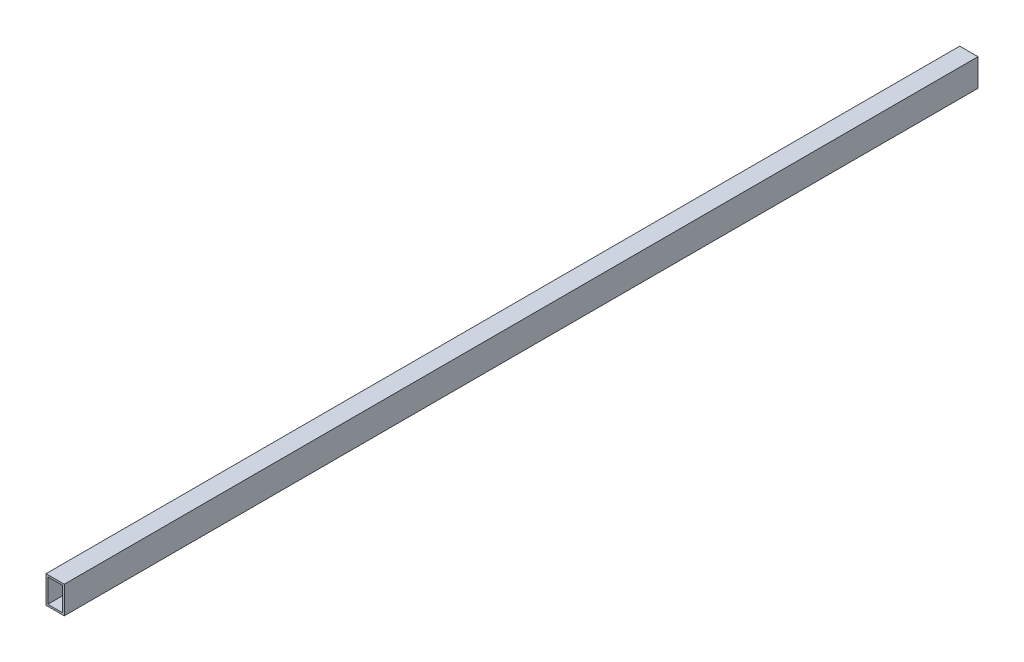
SolidWorks part; units mm, degrees
material "1060 Alloy"
ref_plane "Front Plane" through (0, 0, 0) normal (0, 0, 1) x (1, 0, 0)
ref_plane "Top Plane" through (0, 0, 0) normal (0, 1, 0) x (1, 0, 0)
ref_plane "Right Plane" through (0, 0, 0) normal (1, 0, 0) x (0, 0, -1)
sketch "Sketch1" plane through (0, 0, 0) normal (0, 0, 1) x (1, 0, 0)
  line L0 (-10, 27.5) -> (33, -27.5) construction
  line L1 (33, 27.5) -> (-10, -27.5) construction
  line L2 (3.5, 13) -> (19.5, 13)
  line L3 (1.5, -15) -> (21.5, -15)
  line L4 (1.5, -15) -> (1.5, 15)
  line L5 (1.5, 15) -> (21.5, 15)
  line L6 (21.5, -15) -> (21.5, 15)
  line L7 (1.5, -15) -> (21.5, 15) construction
  line L8 (1.5, 15) -> (21.5, -15) construction
  line L9 (19.5, -13) -> (19.5, 13)
  line L10 (3.5, -13) -> (19.5, -13)
  line L11 (3.5, -13) -> (3.5, 13)
  point P8 (11.5, 0)
  dimension "D1" = 20
  dimension "D2" = 30
  dimension "D3" = 2
extrude "Boss-Extrude1" add sketch "Sketch1" along normal blind 1000
